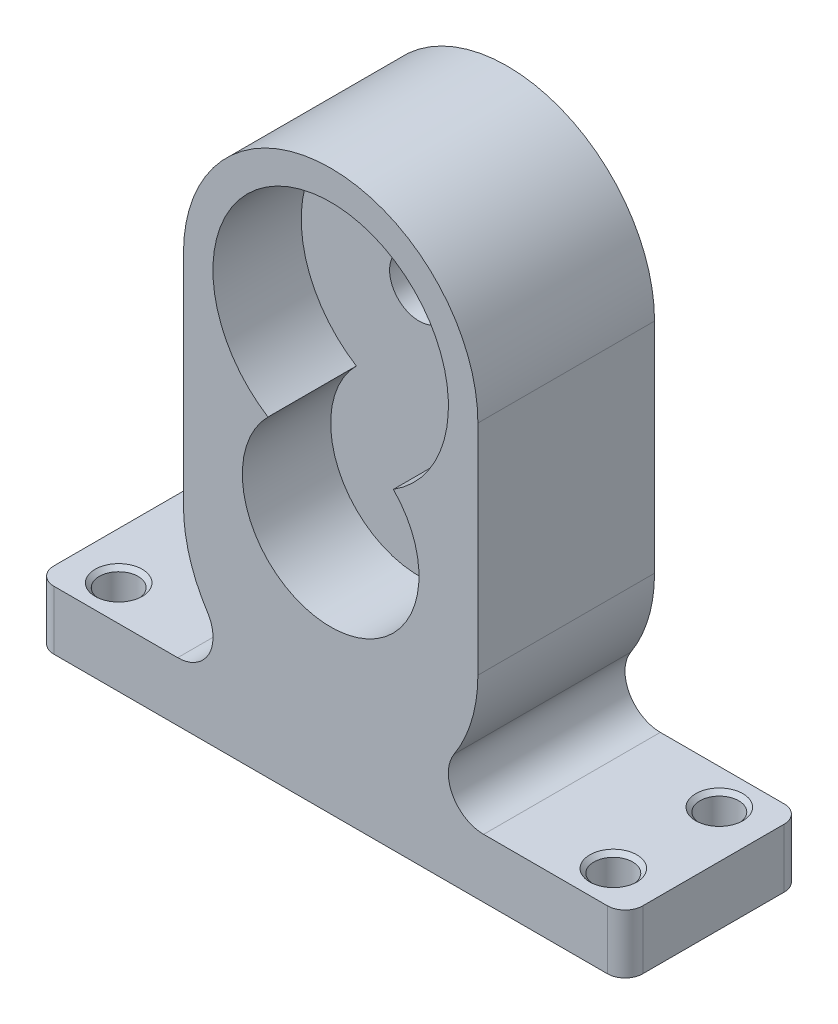
SolidWorks part; units mm, degrees
ref_plane "Спереди" through (0, 0, 0) normal (0, 0, 1) x (1, 0, 0)
ref_plane "Сверху" through (0, 0, 0) normal (0, 1, 0) x (1, 0, 0)
ref_plane "Справа" through (0, 0, 0) normal (1, 0, 0) x (0, 0, -1)
sketch "Эскиз4" plane through (0, 0, 0) normal (0, 0, 1) x (1, 0, 0)
  line L0 (0, 0) -> (50, 0)
  line L1 (50, 0) -> (50, 10)
  line L2 (50, 10) -> (10, 10)
  line L3 (0, 0) -> (0, 95)
  line L6 (25, 70) -> (25, 32.9129)
  arc A2 (0, 95) -> (25, 70) centre (0, 70) cw
  arc A4 (25, 32.9129) -> (10, 10) centre (0, 32.9129) cw
  dimension "D1" = 95
  dimension "D2" = 25
  dimension "D3" = 10
  dimension "D4" = 40
  dimension "D5" = 10
extrude "Бобышка-Вытянуть1" add sketch "Эскиз4" against normal blind 30
mirror "Зеркальное отражение1" about plane through (0, 0, -30) normal (-1, 0, 0) of "Бобышка-Вытянуть1"
sketch "Эскиз5" plane through (0, 0, 0) normal (0, 0, 1) x (1, 0, 0)
  circle A0 centre (0, 70) radius 20
  dimension "D1" = 40
extrude "Вырез-Вытянуть1" cut sketch "Эскиз5" against normal blind 15
sketch "Эскиз6" plane through (0, 0, -15) normal (0, 0, 1) x (1, 0, 0)
  circle A0 centre (0, 70) radius 5
  circle A1 centre (0, 70) radius 20 construction
  dimension "D1" = 10
extrude "Вырез-Вытянуть2" cut sketch "Эскиз6" against normal through all
fillet "Скругление1" radius 6 2 edges at (-10, 10, -15) (10, 10, -15)
sketch "Эскиз7" plane through (0, 0, 0) normal (0, 0, 1) x (1, 0, 0)
  line L1 (0, 0) -> (0, 42.5) construction
  line L2 (-50, 10) -> (-25.9799, 10) construction
  circle A0 centre (0, 42.5) radius 15
  dimension "D1" = 30
  dimension "D2" = 32.5
extrude "Вырез-Вытянуть3" cut sketch "Эскиз7" against normal blind 15
sketch "Эскиз9" plane through (0, 10, 0) normal (0, 1, 0) x (1, 0, 0)
  point P6 (42, 24)
hole_wizard "Зенковка для винта с полупотайной головкой M62" positions "Трехмерный эскиз3" profile "Эскиз11" countersink size "M6" standard "ISO" end condition through all
sketch3d "Трехмерный эскиз3"
  point P0 (42, 10, -24)
sketch "Эскиз11" plane through (42, 10, -24) normal (1, 0, 0) x (0, 0, 1)
  line L0 (0, 0) -> (0, 10)
  line L1 (0, 10) -> (3.3, 10)
  line L2 (3.3, 10) -> (3.3, 0.7)
  line L3 (3.3, 0.7) -> (4, 0)
  line L5 (4, 0) -> (0, 0)
  line L6 (-3.3, 0.7) -> (-4, 0) construction
  line L11 (0, -6.35) -> (0, 107.95) construction
  dimension "Диаметр сквозного отверстия" = 6.6
  dimension "Глубина сквозного отверстия" = 10
  dimension "Диаметр передней зенковки" = 8
  dimension "Угол передней зенковки" = 90
pattern_linear "Линейный массив1" count 2 spacing 18 along (0, 0, 1) count 2 spacing 84 along (-1, 0, 0) of "Зенковка для винта с полупотайной головкой M62"
fillet "Скругление2" radius 3 4 edges at (-50, 5, -30) (-50, 5, 0) (50, 5, 0) (50, 5, -30)
